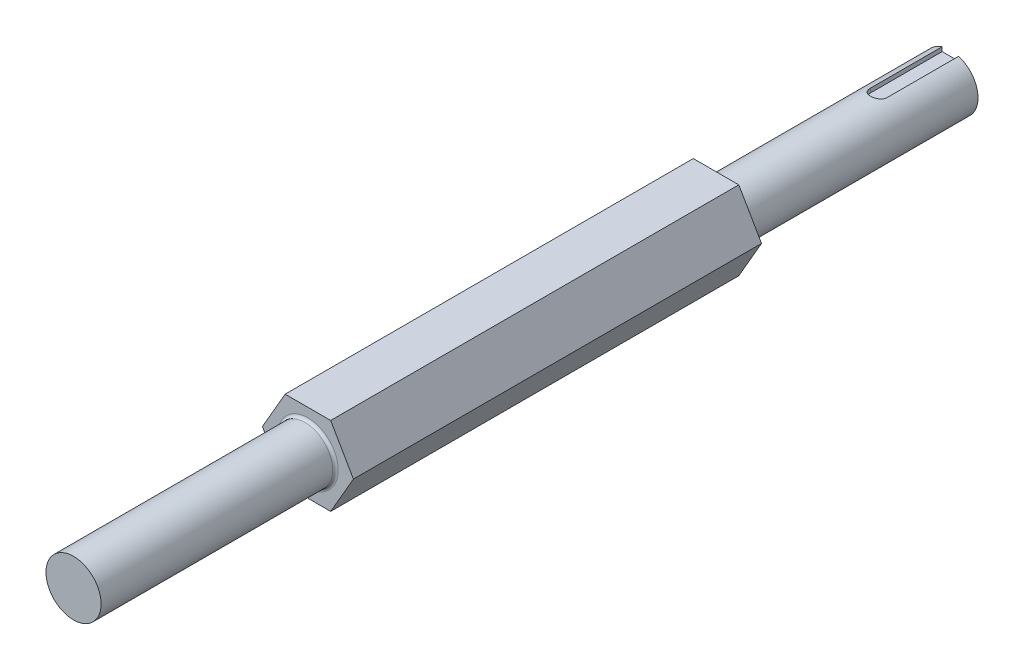
SolidWorks part; units mm, degrees
material "AISI 4130 Steel, annealed at 865C"
ref_plane "Front Plane" through (0, 0, 0) normal (0, 0, 1) x (1, 0, 0)
ref_plane "Top Plane" through (0, 0, 0) normal (0, 1, 0) x (1, 0, 0)
ref_plane "Right Plane" through (0, 0, 0) normal (1, 0, 0) x (0, 0, -1)
sketch "Sketch1" plane through (0, 0, 0) normal (0, 0, 1) x (1, 0, 0)
  line L1 (16.5007, 0) -> (8.2503, 14.29)
  line L2 (8.2503, 14.29) -> (-8.2503, 14.29)
  line L3 (-8.2503, 14.29) -> (-16.5007, 0)
  line L4 (-16.5007, 0) -> (-8.2503, -14.29)
  line L5 (-8.2503, -14.29) -> (8.2503, -14.29)
  line L6 (8.2503, -14.29) -> (16.5007, 0)
  circle A0 centre (0, 0) radius 14.29 construction
  dimension "D1" = 28.58
extrude "Boss-Extrude1" add sketch "Sketch1" along normal mid plane 148
sketch "Sketch2" plane through (0, 0, 74) normal (0, 0, 1) x (1, 0, 0)
  circle A0 centre (0, 0) radius 10
  dimension "D1" = 20
extrude "Boss-Extrude2" add sketch "Sketch2" along normal blind 85
ref_plane "Plane1" through (0, 0, 0) normal (0, 0, 1) x (1, 0, 0)
mirror "Mirror3" about plane through (0, 0, 0) normal (0, 0, 1) of "Boss-Extrude2"
fillet "Fillet1" radius 1 2 edges at (10, 0, 74) (10, 0, -74)
sketch3d "3DSketch1" plane through (0, 0, 0) normal (0, 0, 1) x (1, 0, 0)
sketch "Sketch3" plane through (0, 10, 0) normal (0, 1, 0) x (1, 0, 0)
  line L1 (3, 159) -> (3, 133)
  line L2 (10, 159) -> (-10, 159) construction
  line L3 (-3, 159) -> (-3, 133)
  line L4 (-3, 159) -> (3, 159)
  arc A0 (-3, 133) -> (3, 133) centre (0, 133) ccw
  dimension "D2" = 26
  dimension "D3" = 26
extrude "Cut-Extrude1" cut sketch "Sketch3" against normal blind 2
